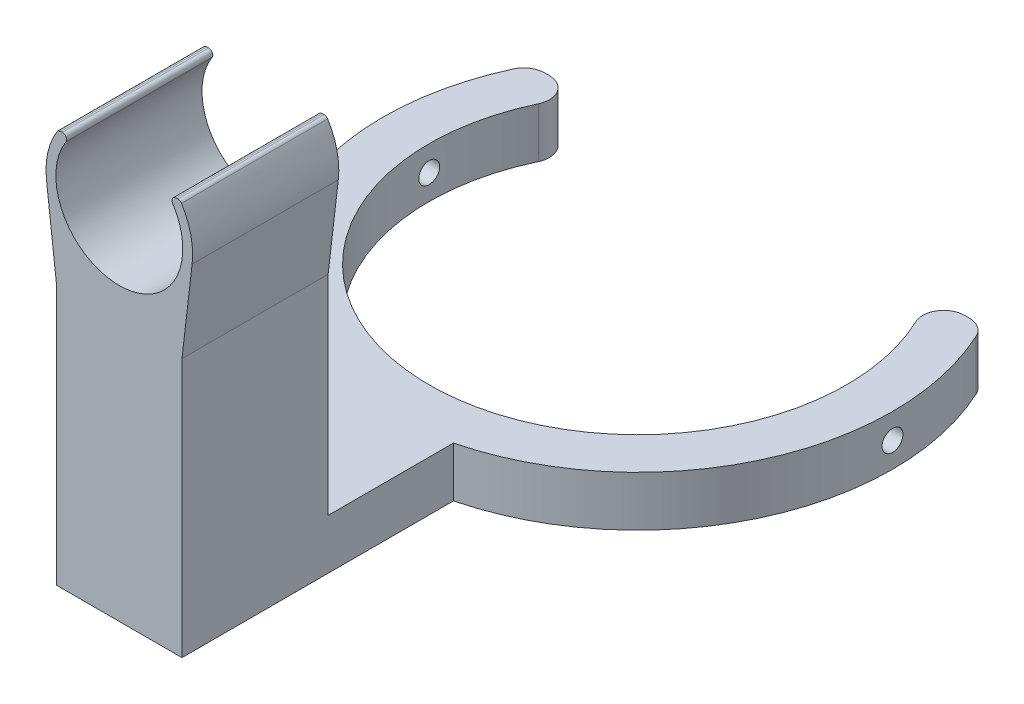
SolidWorks part; units mm, degrees
ref_plane "前视基准面" through (0, 0, 0) normal (0, 0, 1) x (1, 0, 0)
ref_plane "上视基准面" through (0, 0, 0) normal (0, 1, 0) x (1, 0, 0)
ref_plane "右视基准面" through (0, 0, 0) normal (1, 0, 0) x (0, 0, -1)
sketch "Sketch1" plane through (0, 0, 0) normal (0, 1, 0) x (1, 0, 0)
  line L0 (0, 0) -> (0, 37.0754) construction
  line L2 (-53.9518, 28.5363) -> (-41.057, 28.5363)
  line L3 (41.057, 28.5363) -> (53.9518, 28.5363)
  line L4 (-15, -59.1618) -> (15, -59.1618)
  line L5 (15, -59.1618) -> (15, -124.1618)
  line L6 (15, -124.1618) -> (-15, -124.1618)
  line L7 (-15, -124.1618) -> (-15, -59.1618)
  arc A0 (-41.057, 28.5363) -> (41.057, 28.5363) centre (0, 0) ccw
  arc A2 (-53.9518, 28.5363) -> (53.9518, 28.5363) centre (0, 0) ccw
  dimension "D1" = 30
  dimension "D2" = 50
  dimension "D3" = 65
extrude "Boss-Extrude1" add sketch "Sketch1" along normal blind 12 contours L4 A2 L3 A0 L2 | A2 L7 L6 L5 | L4 A2
sketch "Sketch2" plane through (15, 0, 0) normal (1, 0, 0) x (0, 0, -1)
  line L0 (-59.1618, 12) -> (-59.1618, 0) construction
  line L1 (-59.1618, 0) -> (-59.1618, 6) construction
  line L2 (-59.1618, 6) -> (66.3346, 6) construction
  line L3 (0, 0) -> (0, 12) construction
  line L4 (28.5363, 12) -> (-59.1618, 12) construction
  circle A0 centre (0, 6) radius 2.5
extrude "Cut-Extrude1" cut sketch "Sketch2" against normal mid plane 1000
sketch "Sketch4" plane through (-15, 0, 0) normal (-1, 0, 0) x (0, 0, 1)
  line L0 (124.1618, 12) -> (124.1618, 62)
  line L1 (124.1618, 62) -> (89.1618, 62)
  line L2 (89.1618, 62) -> (89.1618, 12)
  line L3 (124.1618, 12) -> (59.1618, 12) construction
  line L4 (89.1618, 12) -> (124.1618, 12)
  dimension "D1" = 50
  dimension "D2" = 35
extrude "Boss-Extrude2" add sketch "Sketch4" against normal up to surface (30 mm away) up to face at (15, 6, 91.6618)
sketch "Sketch5" plane through (0, 0, 124.1618) normal (0, 0, 1) x (1, 0, 0)
  line L0 (-14.5864, 94.6356) -> (-11.6439, 94.6356)
  line L1 (11.6439, 94.6356) -> (14.5864, 94.6356)
  line L2 (-15, 62) -> (-17.4373, 82.8244)
  line L3 (15, 62) -> (17.4373, 82.8244)
  arc A1 (-11.6439, 94.6356) -> (11.6439, 94.6356) centre (0, 84.8653) ccw
  arc A2 (-14.5864, 94.6356) -> (14.5864, 94.6356) centre (0, 84.8653) ccw
  point P2 (0, 69.6653)
  dimension "D1" = 15.2
extrude "Boss-Extrude3" add sketch "Sketch5" against normal up to surface (35 mm away)
fillet "Fillet1" radius 5 4 edges at (53.9518, 6, -28.5363) (41.057, 6, -28.5363) (-53.9518, 6, -28.5363) (-41.057, 6, -28.5363)
fillet "Fillet2" radius 1 2 edges at (11.6439, 94.6356, 106.6618) (-11.6439, 94.6356, 106.6618)
sketch "Sketch6" plane through (0, 0, 89.1618) normal (0, 0, -1) x (-1, 0, 0)
  line L0 (-13.657, 91.538) -> (13.657, 91.538) construction
  arc A1 (-13.657, 91.538) -> (13.657, 91.538) centre (0, 84.8653) ccw
  arc A2 (-12.7798, 93.0943) -> (12.7798, 93.0943) centre (0, 84.8653) ccw construction
fillet "圆角1" radius 1 2 edges at (14.5864, 94.6356, 106.6618) (-14.5864, 94.6356, 106.6618)
